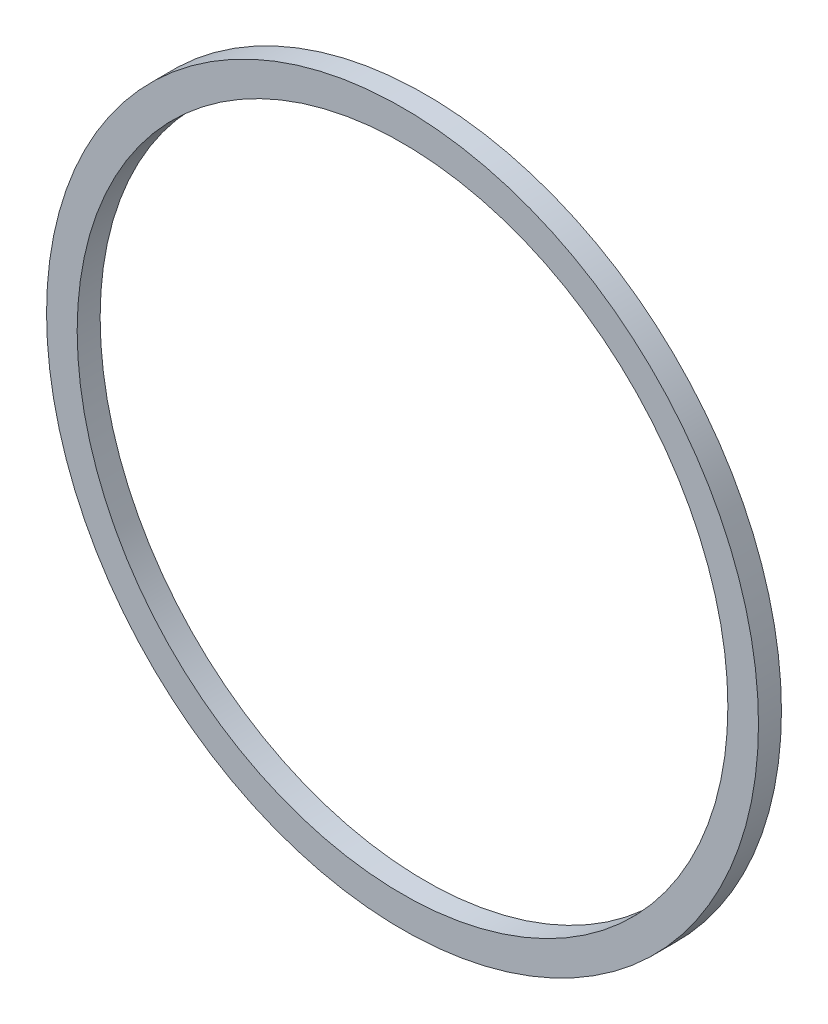
SolidWorks part; units mm, degrees
ref_plane "Front Plane" through (0, 0, 0) normal (0, 0, 1) x (1, 0, 0)
ref_plane "Top Plane" through (0, 0, 0) normal (0, 1, 0) x (1, 0, 0)
ref_plane "Right Plane" through (0, 0, 0) normal (1, 0, 0) x (0, 0, -1)
sketch "Sketch1" plane through (0, 0, 0) normal (0, 0, 1) x (1, 0, 0)
  circle A0 centre (0, 0) radius 46.5
  circle A1 centre (0, 0) radius 42.5
  dimension "D1" = 93
  dimension "D2" = 85
extrude "Boss-Extrude1" add sketch "Sketch1" along normal mid plane 3
